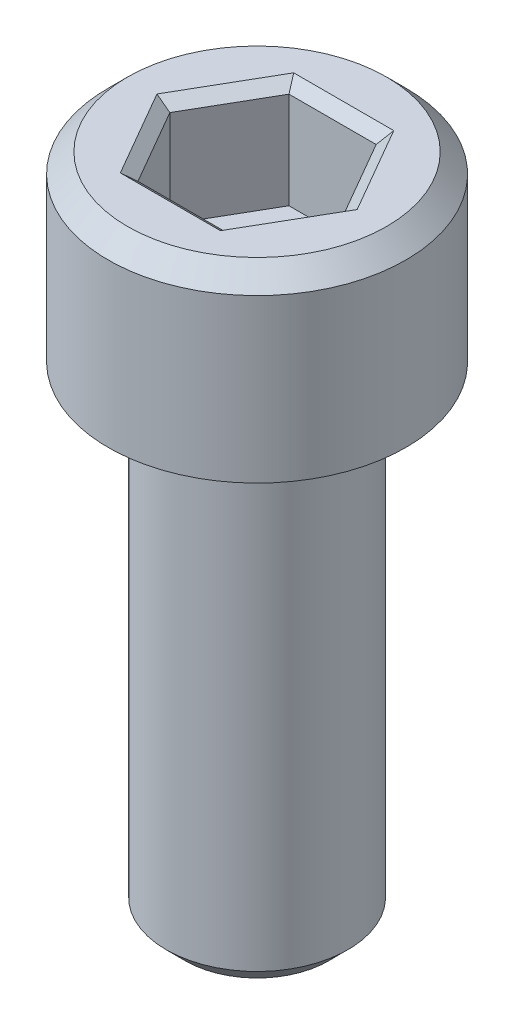
SolidWorks part; units mm, degrees
material "Galvanized Steel"
ref_plane "Front Plane" through (0, 0, 0) normal (0, 0, 1) x (1, 0, 0)
ref_plane "Top Plane" through (0, 0, 0) normal (0, 1, 0) x (1, 0, 0)
ref_plane "Right Plane" through (0, 0, 0) normal (1, 0, 0) x (0, 0, -1)
sketch "Sketch1" plane through (0, 0, 0) normal (0, 0, 1) x (1, 0, 0)
  line L0 (0, 0) -> (0, 14.6665) construction
  line L1 (0, 0) -> (0, 17.4752)
  line L2 (0, 17.4752) -> (-3.9116, 17.4752)
  line L3 (-3.9116, 17.4752) -> (-3.9116, 12.7)
  line L4 (-3.9116, 12.7) -> (-2.3876, 12.7)
  line L5 (-2.3876, 12.7) -> (-2.3876, 0)
  line L6 (-2.3876, 0) -> (0, 0)
  dimension "D1" = 12.7
  dimension "D2" = 4.7752
  dimension "D3" = 17.4752
  dimension "D4" = 7.8232
revolve "Revolve1" add sketch "Sketch1" angle 360 about L0
sketch "Sketch2" plane through (0, 17.4752, 0) normal (0, 1, 0) x (1, 0, 0)
  line L0 (0, 0) -> (2.3879, 0) construction
  line L1 (2.2914, 0) -> (1.1457, 1.9844)
  line L2 (1.1457, 1.9844) -> (-1.1457, 1.9844)
  line L3 (-1.1457, 1.9844) -> (-2.2914, 0)
  line L4 (-2.2914, 0) -> (-1.1457, -1.9844)
  line L5 (-1.1457, -1.9844) -> (1.1457, -1.9844)
  line L6 (1.1457, -1.9844) -> (2.2914, 0)
  circle A0 centre (0, 0) radius 1.9844 construction
  dimension "D1" = 4.5827
extrude "Extrude1" cut sketch "Sketch2" against normal blind 2.794
chamfer "Chamfer1" distance 0.508 angle 45 2 edges at (0, 17.4752, -3.9116) (0, 0, -2.3876)
chamfer "Chamfer2" distance 0.2933 angle 40.893 6 edges at (0, 17.4752, -1.9844) (1.7185, 17.4752, -0.9922) (1.7185, 17.4752, 0.9922) (0, 17.4752, 1.9844) (-1.7185, 17.4752, -0.9922) (-1.7185, 17.4752, 0.9922)
